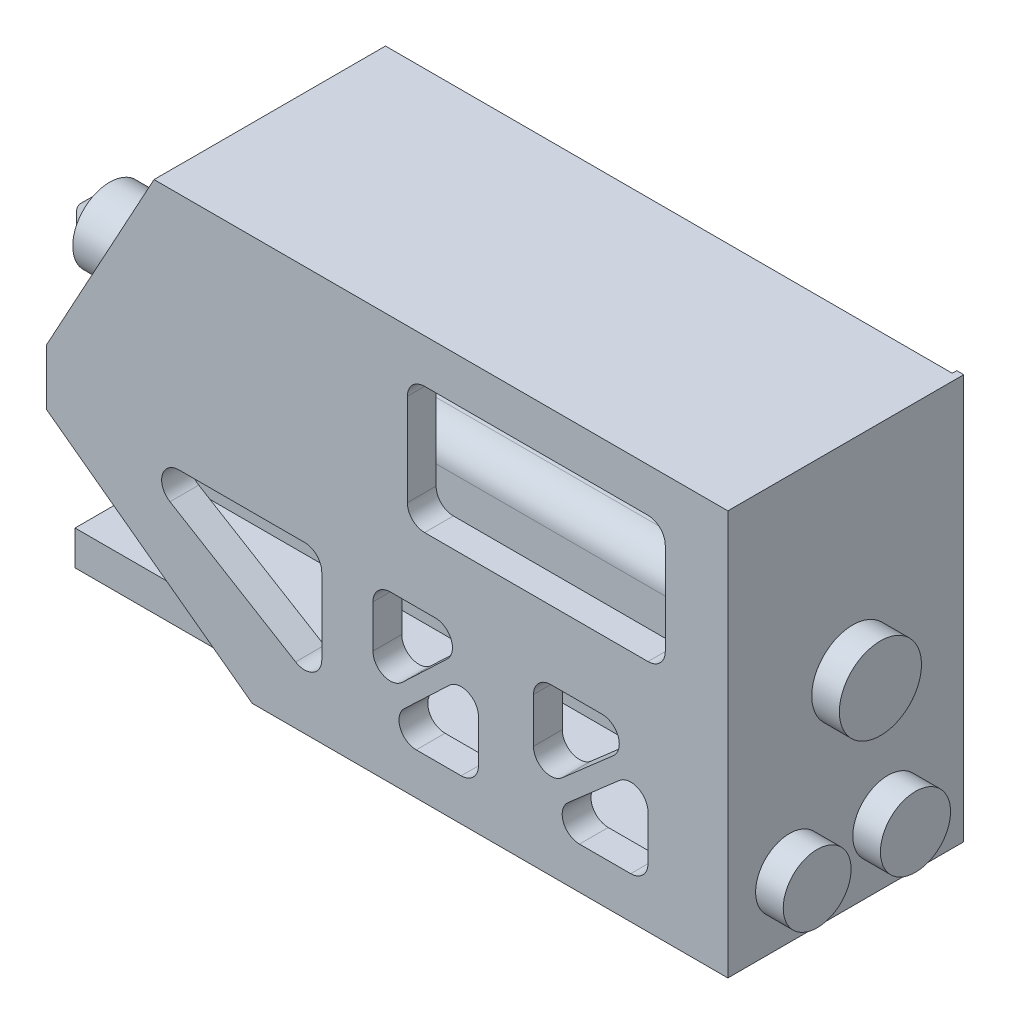
SolidWorks part; units mm, degrees
ref_plane "Front Plane" through (0, 0, 0) normal (0, 0, 1) x (1, 0, 0)
ref_plane "Top Plane" through (0, 0, 0) normal (0, 1, 0) x (1, 0, 0)
ref_plane "Right Plane" through (0, 0, 0) normal (1, 0, 0) x (0, 0, -1)
sketch "Sketch1" plane through (0, 0, 0) normal (0, 1, 0) x (1, 0, 0)
  line L1 (0, 0) -> (297.7363, 0)
  line L2 (0, 0) -> (0, 182.7784)
  line L3 (0, 182.7784) -> (297.7363, 182.7784)
  line L4 (297.7363, 0) -> (297.7363, 182.7784)
extrude "Boss-Extrude1" add sketch "Sketch1" along normal blind 15.24
sketch "Sketch2" plane through (0, 0, 0) normal (-1, 0, 0) x (0, 0, 1)
  line L0 (-139.3241, 0) -> (-113.9241, 0)
  line L1 (-182.7784, 0) -> (-139.3241, 0)
  line L2 (-182.7784, 0) -> (0, 0) construction
  line L3 (-91.3892, 0) -> (-91.3892, 15.24) construction
  line L4 (-182.7784, 15.24) -> (0, 15.24) construction
  line L5 (-139.3241, 0) -> (-126.6241, 0)
  line L6 (-43.4543, 0) -> (-68.8543, 0)
  arc A0 (-113.9241, 0) -> (-139.3241, 0) centre (-126.6241, 0) ccw
  arc A1 (-68.8543, 0) -> (-43.4543, 0) centre (-56.1543, 0) cw
  line M4 (-182.7784, 0) -> (0, 0)
extrude "Cut-Extrude1" cut sketch "Sketch2" against normal through all contours A1 M4 | L0 A0 M4
sketch "Sketch4" plane through (0, 0, 0) normal (-1, 0, 0) x (0, 0, 1)
  line L0 (-113.9241, 0) -> (-68.8543, 0) construction
  line L7 (-91.3892, 0) -> (-182.7784, 0)
  line L9 (-91.3892, 0) -> (-91.3892, 15.24)
  line L12 (-91.3892, 0) -> (-91.3892, 15.24)
  line L13 (-91.3892, 15.24) -> (-182.7784, 15.24)
  line L14 (-182.7784, 0) -> (-182.7784, 15.24)
  point P0 (-91.3892, 0)
  line M4 (0, 15.24) -> (-182.7784, 15.24)
  line M5 (-182.7784, 15.24) -> (-182.7784, 0)
  line M6 (-182.7784, 0) -> (-139.3241, 0)
  arc M7 (-139.3241, 0) -> (-113.9241, 0) centre (-126.6241, 0) cw
  line M8 (-113.9241, 0) -> (-68.8543, 0)
extrude "Cut-Extrude2" cut sketch "Sketch4" against normal through all contours L9 M8 M4 M5 M6 M7
sketch "Sketch5" plane through (0, 15.24, 0) normal (0, 1, 0) x (1, 0, 0)
  line L0 (0, 91.3892) -> (0, 0) construction
  line L1 (297.7363, 91.3892) -> (0, 91.3892)
  line L2 (297.7363, 91.3892) -> (297.7363, 40.6863)
  line L3 (297.7363, 40.6863) -> (0, 40.6863)
  line L4 (0, 91.3892) -> (0, 40.6863)
extrude "Boss-Extrude2" add sketch "Sketch5" along normal blind 76.2
fillet "Fillet1" radius 12.7 1 edges at (148.8681, 91.44, -91.3892)
fillet "Fillet2" radius 12.7 1 edges at (148.8681, 91.44, -40.6863)
sketch "Sketch6" plane through (0, 0, 0) normal (-1, 0, 0) x (0, 0, 1)
  line L0 (-66.0377, 91.44) -> (-66.0377, 0) construction
  line L1 (-78.6892, 91.44) -> (-53.3863, 91.44) construction
  circle A0 centre (-66.0377, 72.7348) radius 16.2458
extrude "Boss-Extrude3" add sketch "Sketch6" along normal blind 50.8
sketch "Sketch7" plane through (-50.8, 0, 0) normal (-1, 0, 0) x (0, 0, 1)
  line L0 (-66.0377, 88.9805) -> (-66.0377, 56.489) construction
  circle A0 centre (-66.0377, 72.7348) radius 16.2458 construction
  circle A1 centre (-66.0377, 72.7348) radius 11.8138
extrude "Boss-Extrude4" add sketch "Sketch7" along normal blind 12.7
chamfer "Chamfer1" distance 10 angle 45 1 edges at (-63.5, 72.7348, -54.2239)
sketch "Sketch8" plane through (-63.5, 0, 0) normal (-1, 0, 0) x (0, 0, 1)
  line L0 (-66.0377, 74.5486) -> (-66.0377, 70.921) construction
  circle A0 centre (-66.0377, 72.7348) radius 1.8138 construction
  circle A1 centre (-66.0377, 72.7348) radius 1.2488
extrude "Cut-Extrude3" cut sketch "Sketch8" against normal blind 12.7
sketch "Sketch9" plane through (0, 0, 0) normal (0, 0, 1) x (1, 0, 0)
  line L1 (297.7363, 0) -> (90.8944, 0)
  line L2 (297.7363, 0) -> (297.7363, 178.5322)
  line L3 (297.7363, 178.5322) -> (90.8944, 178.5322)
  line L6 (90.8944, 178.5322) -> (47.551, 178.5322)
  line L7 (47.551, 178.5322) -> (0, 91.44)
  line L8 (0, 91.44) -> (0, 67.007)
  line L9 (0, 78.74) -> (0, 15.24) construction
  line L10 (0, 67.007) -> (90.8944, 0)
  line L11 (58.531, 73.0706) -> (113.9612, 73.0706)
  line L12 (265.5392, 159.2086) -> (166.9552, 159.2086)
  line L13 (273.1592, 151.5886) -> (273.1592, 110.9365)
  line L14 (265.5392, 103.3165) -> (166.9552, 103.3165)
  line L15 (159.3352, 151.5886) -> (159.3352, 110.9365)
  line L16 (121.5812, 65.4506) -> (121.5812, 31.9443)
  line L17 (110.0193, 25.4231) -> (54.5891, 58.9294)
  line L18 (144.1777, 65.4506) -> (144.1777, 46.6294)
  line L19 (157.0439, 41.1029) -> (176.8709, 59.9241)
  line L20 (171.6247, 73.0706) -> (151.7977, 73.0706)
  line L21 (183.0999, 18.4342) -> (163.2729, 18.4342)
  line L22 (158.0267, 31.5807) -> (177.8537, 50.402)
  line L23 (190.7199, 44.8755) -> (190.7199, 26.0542)
  line L24 (215.0027, 65.4506) -> (215.0027, 45.6725)
  line L25 (227.6381, 39.9357) -> (250.2611, 59.7138)
  line L26 (245.2458, 73.0706) -> (222.6227, 73.0706)
  line L27 (235.2961, 18.4342) -> (257.9192, 18.4342)
  line L28 (265.5392, 18.4342) -> (215.0027, 18.4342)
  line L29 (230.2808, 31.791) -> (252.9039, 51.5691)
  line L30 (265.5392, 45.8323) -> (265.5392, 26.0542)
  line L31 (90.8944, 0) -> (297.7363, 0)
  line L32 (297.7363, 178.5322) -> (297.7363, 0)
  line L33 (90.8944, 0) -> (297.7363, 0)
  line L34 (297.7363, 178.5322) -> (297.7363, 0)
  arc A0 (166.9552, 159.2086) -> (159.3352, 151.5886) centre (166.9552, 151.5886) ccw
  arc A1 (166.9552, 103.3165) -> (159.3352, 110.9365) centre (166.9552, 110.9365) cw
  arc A2 (265.5392, 103.3165) -> (273.1592, 110.9365) centre (265.5392, 110.9365) ccw
  arc A3 (273.1592, 151.5886) -> (265.5392, 159.2086) centre (265.5392, 151.5886) ccw
  arc A4 (110.0193, 25.4231) -> (121.5812, 31.9443) centre (113.9612, 31.9443) ccw
  arc A6 (54.5891, 58.9294) -> (58.531, 73.0706) centre (58.531, 65.4506) cw
  arc A7 (121.5812, 65.4506) -> (113.9612, 73.0706) centre (113.9612, 65.4506) ccw
  arc A8 (157.0439, 41.1029) -> (144.1777, 46.6294) centre (151.7977, 46.6294) cw
  arc A9 (176.8709, 59.9241) -> (171.6247, 73.0706) centre (171.6247, 65.4506) ccw
  arc A10 (151.7977, 73.0706) -> (144.1777, 65.4506) centre (151.7977, 65.4506) ccw
  arc A11 (163.2729, 18.4342) -> (158.0267, 31.5807) centre (163.2729, 26.0542) cw
  arc A12 (183.0999, 18.4342) -> (190.7199, 26.0542) centre (183.0999, 26.0542) ccw
  arc A13 (190.7199, 44.8755) -> (177.8537, 50.402) centre (183.0999, 44.8755) ccw
  arc A14 (227.6381, 39.9357) -> (215.0027, 45.6725) centre (222.6227, 45.6725) cw
  arc A15 (245.2458, 73.0706) -> (250.2611, 59.7138) centre (245.2458, 65.4506) cw
  arc A16 (222.6227, 73.0706) -> (215.0027, 65.4506) centre (222.6227, 65.4506) ccw
  arc A17 (235.2961, 18.4342) -> (230.2808, 31.791) centre (235.2961, 26.0542) cw
  arc A18 (265.5392, 26.0542) -> (257.9192, 18.4342) centre (257.9192, 26.0542) cw
  arc A19 (265.5392, 45.8323) -> (252.9039, 51.5691) centre (257.9192, 45.8323) ccw
  point P40 (121.5812, 18.4342)
  point P58 (190.7199, 18.4342)
  dimension "D1" = 7.62
  dimension "D2" = 7.62
  dimension "D3" = 7.62
  dimension "D4" = 7.62
  dimension "D5" = 7.62
  dimension "D6" = 7.62
  dimension "D7" = 7.62
  dimension "D8" = 7.62
extrude "Boss-Extrude5" add sketch "Sketch9" along normal blind 12.7
sketch "Sketch10" plane through (0, 0, 0) normal (0, 0, -1) x (-1, 0, 0)
  line L0 (-47.5843, 178.5322) -> (0, 91.44)
  line L1 (-297.7363, 178.5322) -> (-47.5843, 178.5322)
  line L2 (-297.7363, 178.5322) -> (-297.7363, 172.6909)
  line L3 (-297.7363, 172.6909) -> (-52.6132, 172.6909)
  line L5 (0, 91.44) -> (-8.2204, 91.44)
  line L6 (-8.2204, 91.44) -> (-52.6132, 172.6909)
extrude "Boss-Extrude6" add sketch "Sketch10" along normal blind 89.408
sketch "Sketch11" plane through (297.7363, 0, 0) normal (1, 0, 0) x (0, 0, -1)
  line L1 (-12.7, 178.5322) -> (91.3892, 178.5322)
  line L2 (-12.7, 178.5322) -> (-12.7, 0)
  line L3 (-12.7, 0) -> (91.3892, 0)
  line L4 (91.3892, 178.5322) -> (91.3892, 0)
extrude "Boss-Extrude7" add sketch "Sketch11" along normal blind 3.048
sketch "Sketch12" plane through (300.7843, 0, 0) normal (1, 0, 0) x (0, 0, -1)
  circle A0 centre (57.906, 26.6494) radius 15.4758
  circle A1 centre (42.4301, 89.2661) radius 18.1141
  circle A2 centre (14.5216, 26.6494) radius 14.9833
extrude "Boss-Extrude8" add sketch "Sketch12" along normal blind 12.192
